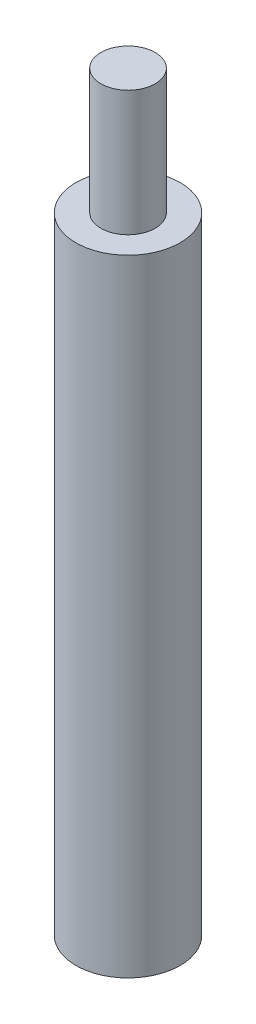
SolidWorks part; units mm, degrees
ref_plane "Front Plane" through (0, 0, 0) normal (0, 0, 1) x (1, 0, 0)
ref_plane "Top Plane" through (0, 0, 0) normal (0, 1, 0) x (1, 0, 0)
ref_plane "Right Plane" through (0, 0, 0) normal (1, 0, 0) x (0, 0, -1)
sketch "Sketch1" plane through (0, 0, 0) normal (0, 1, 0) x (1, 0, 0)
  circle A0 centre (0, 0) radius 6.35
  dimension "D1" = 12.7
extrude "Boss-Extrude1" add sketch "Sketch1" along normal blind 76.2 contours A0
sketch "Sketch2" plane through (0, 76.2, 0) normal (0, 1, 0) x (1, 0, 0)
  circle A0 centre (0, 0) radius 3.302
  dimension "D1" = 6.604
extrude "Boss-Extrude2" add sketch "Sketch2" along normal blind 15.24
